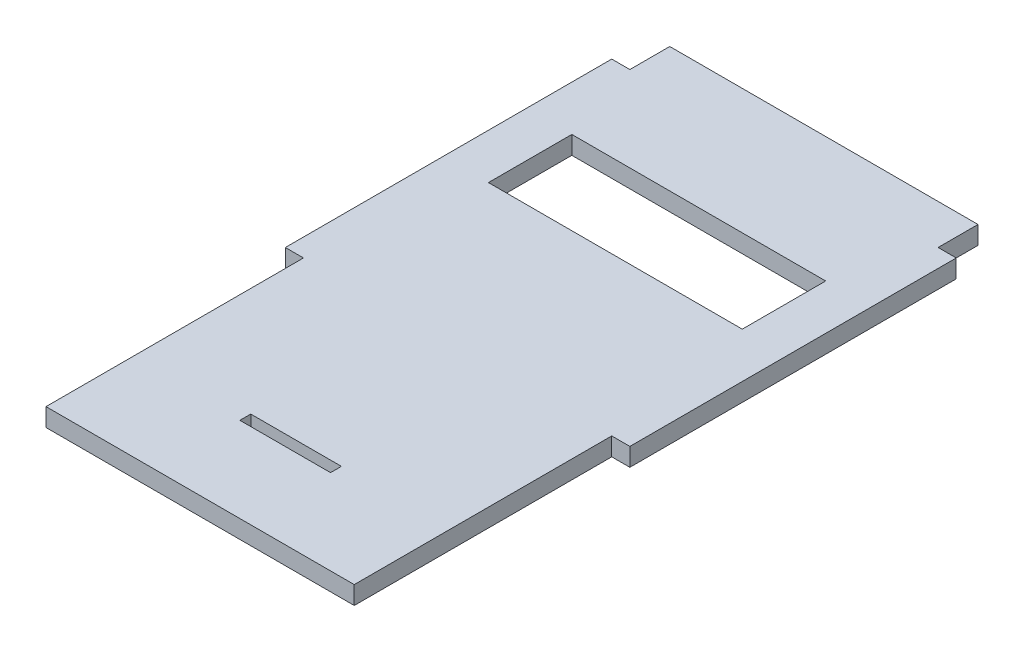
SolidWorks part; units mm, degrees
ref_plane "Alzado" through (0, 0, 0) normal (0, 0, 1) x (1, 0, 0)
ref_plane "Planta" through (0, 0, 0) normal (0, 1, 0) x (1, 0, 0)
ref_plane "Vista lateral" through (0, 0, 0) normal (1, 0, 0) x (0, 0, -1)
sketch "Croquis1" plane through (0, 0, 0) normal (0, 1, 0) x (1, 0, 0)
  line L0 (-42.5, -15) -> (42.5, -15) construction
  line L1 (-42.5, -86) -> (42.5, -86)
  line L2 (-42.5, -86) -> (-42.5, -15)
  line L3 (-42.5, 86) -> (42.5, 86)
  line L4 (42.5, -86) -> (42.5, -15)
  line L5 (-42.5, -86) -> (42.5, 86) construction
  line L6 (-42.5, 86) -> (42.5, -86) construction
  line L7 (-42.5, 75) -> (-42.5, 86)
  line L8 (-42.5, -15) -> (-47.5, -15)
  line L9 (42.5, 75) -> (42.5, 86)
  line L10 (-42.5, 75) -> (-47.5, 75)
  line L11 (-47.5, -15) -> (-47.5, 75)
  line L12 (42.5, 75) -> (47.5, 75)
  line L13 (0, 86) -> (0, -86) construction
  line L14 (42.5, -15) -> (47.5, -15)
  line L15 (47.5, 75) -> (47.5, -15)
  line L17 (-12.5, -62.5396) -> (12.5, -62.5396)
  line L18 (-12.5, -62.5396) -> (-12.5, -59.5396)
  line L19 (-12.5, -59.5396) -> (12.5, -59.5396)
  line L20 (12.5, -62.5396) -> (12.5, -59.5396)
  line L21 (-12.5, -62.5396) -> (12.5, -59.5396) construction
  line L22 (-12.5, -59.5396) -> (12.5, -62.5396) construction
  line L23 (-35, 28.5) -> (35, 28.5)
  line L24 (-35, 28.5) -> (-35, 51.5)
  line L25 (-35, 51.5) -> (35, 51.5)
  line L26 (35, 28.5) -> (35, 51.5)
  line L27 (-35, 28.5) -> (35, 51.5) construction
  line L28 (-35, 51.5) -> (35, 28.5) construction
  point P0 (0, 0)
  point P16 (0, -61.0396)
  point P21 (0, 40)
  dimension "D1" = 172
  dimension "D2" = 85
  dimension "D3" = 71
  dimension "D4" = 90
  dimension "D5" = 5
  dimension "D6" = 5
  dimension "D7" = 25
  dimension "D8" = 3
  dimension "D9" = 70
  dimension "D10" = 23
  dimension "D11" = 40
extrude "Saliente-Extruir1" add sketch "Croquis1" along normal blind 5
